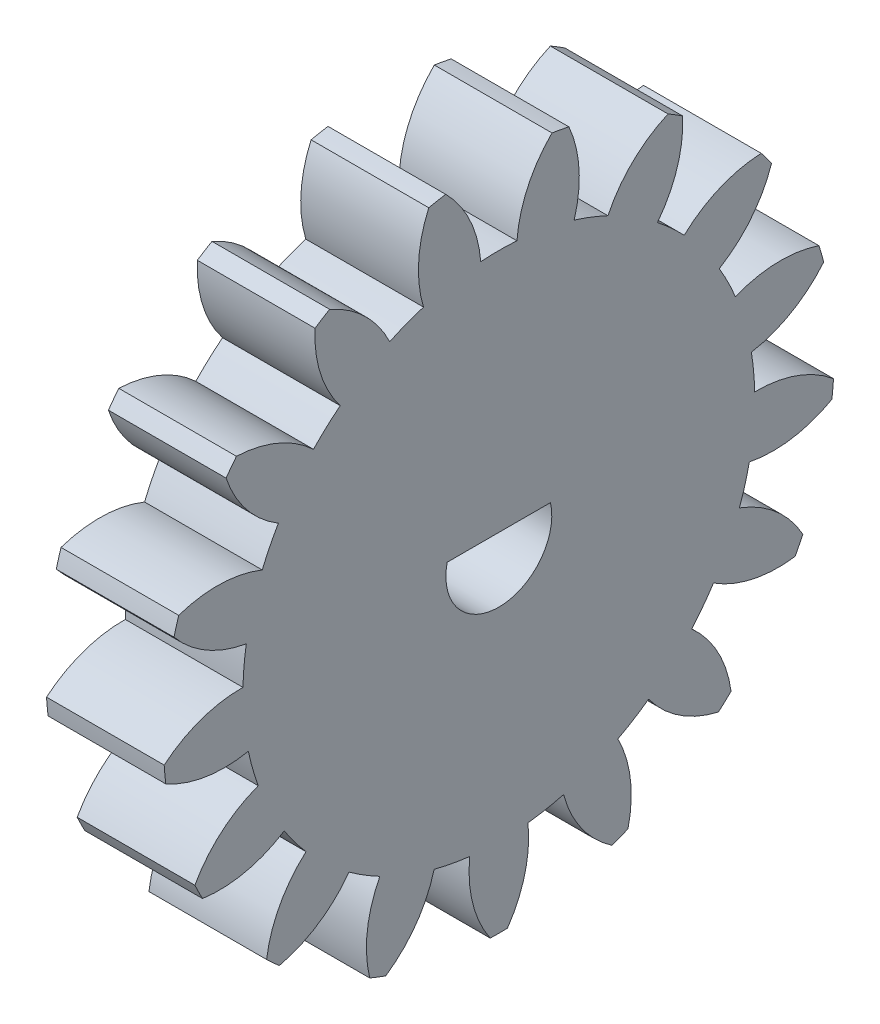
SolidWorks part; units mm, degrees
ref_plane "Plane1" through (0, 0, 0) normal (0, 0, 1) x (1, 0, 0)
ref_plane "Plane2" through (0, 0, 0) normal (0, 1, 0) x (1, 0, 0)
ref_plane "Plane3" through (0, 0, 0) normal (1, 0, 0) x (0, 0, -1)
sketch "HoldingSke" plane through (0, 0, 0) normal (0, 1, 0) x (1, 0, 0)
  line L0 (0, 0) -> (0.6375, -0.1949)
  line L1 (-15, 0) -> (100, 0) construction
  line L2 (0, 0) -> (-2.1039, 2.3779)
  line L3 (0, 0) -> (-11.863, 4.5341)
  line L4 (0, 0) -> (8.2586, 2.5249)
  line L5 (0, 0) -> (-46.8476, -17.4728)
  line L6 (0, 0) -> (-4.1448, -2.7965)
  line L7 (-2.1039, 2.3779) -> (8.6586, 51.2059)
  line L8 (-76.2, 54.61) -> (-76.1, 54.61)
  line L9 (-71.009, 38.7566) -> (-53.1078, 45.2721)
  line L10 (-76.2, 71.12) -> (104.1128, 71.12)
  line L11 (0, 0) -> (-5, 0)
  line L12 (-76.2, 101.6) -> (-76.147, 101.6)
  line L13 (24.9733, 27.94) -> (52.9518, 28.4284)
  line L14 (24.9733, 27.94) -> (24.9743, 27.94)
  line L15 (24.9733, 27.94) -> (100.4006, 29.5858)
  line L16 (-63.627, -1.5) -> (-12.827, -1.5)
  circle A0 centre (0, 0) radius 0.4
  circle A1 centre (0, 0) radius 10.874
  circle A2 centre (0, 0) radius 37.5
  circle A3 centre (0, 0) radius 0.4
  dimension "MHD" = 21.748
  dimension "Hub_dia" = 75
  dimension "Bore" = 0.8
  dimension "MBD" = 0.8
  dimension "Num_teeth" = 17
  dimension "Pitch" = 0.6667
  dimension "Overall_len" = 50
  dimension "Show_teeth" = 17
  dimension "Thickness" = 5
  dimension "OAL" = 50.0001
  dimension "T_dim" = 0.1
  dimension "Ap" = 20
  dimension "H" = 19.05
  dimension "Pitch_radius" = 180.3128
  dimension "Width" = 5
  dimension "Backlash" = 0.053
  dimension "Addendum_fac" = 1
  dimension "Dedendum_fac" = 1.25
  dimension "Clearance_fac" = 0.25
  dimension "Dedendum_add" = 0.001
  dimension "Module" = 1.5
sketch "BasProSke" plane through (0, 0, 0) normal (0, 1, 0) x (1, 0, 0)
  line L0 (-10, 0) -> (60, 0) construction
  line L1 (0, 0) -> (0, 14.25)
  line L2 (0, 0) -> (5, 0)
  line L3 (5, 0) -> (5, 14.25)
  line L4 (5, 14.25) -> (0, 14.25)
  dimension "Thickness" = 5
  dimension "Diameter" = 28.5
revolve "Base-Revolve" add sketch "BasProSke" angle 360 about L0
sketch "TooCutSke" plane through (0, 0, 0) normal (1, 0, 0) x (0, 0, -1)
  line L1 (0, 0) -> (0, 107) construction
  line L2 (0, 0) -> (-1.2691, 12.6867) construction
  line L3 (0, 0) -> (-4.6687, 24.9751) construction
  line L4 (-1.2691, 12.6867) -> (-2.3343, 12.4876) construction
  arc A0 (0.7694, 10.8467) -> (-0.7694, 10.8467) centre (0, 0) ccw
  arc A1 (2.2806, 14.0921) -> (-2.2806, 14.0921) centre (0, 0) ccw
  circle A2 centre (0, 0) radius 12.75 construction
  circle A3 centre (0, 0) radius 11.9811 construction
  arc A4 (-0.7694, 10.8467) -> (-2.2806, 14.0921) centre (-5.8542, 10.4535) ccw
  arc A5 (2.2806, 14.0921) -> (0.7694, 10.8467) centre (5.8542, 10.4535) ccw
  dimension "Root_dia" = 21.748
  dimension "Overcut_dia" = 28.5508
  dimension "Pitch_dia" = 25.5
  dimension "Base_dia" = 23.9622
  dimension "Flank_rad" = 5.1
  dimension "Half_ang" = 10.588
  dimension "Half_CT" = 1.0837
extrude "ToothCut" cut sketch "TooCutSke" along normal through all
fillet "Breaks" [suppressed] radius 0.03
fillet "RootFillets" [suppressed] radius 0.376
pattern_circular "TeethCuts" count 17 every 21.176 about axis through (-10, 0, 0) along (1, 0, 0) of "ToothCut", "RootFillets", "Breaks"
sketch "HubNeaOneSke" plane through (0, 0, 0) normal (-1, 0, 0) x (0, 0, 1)
  circle A0 centre (0, 0) radius 10.874
  dimension "Diameter" = 21.748
extrude "HubNearOne" [suppressed] add sketch "HubNeaOneSke" along normal blind 45.0001
sketch "HubNeaBotSke" plane through (0, 0, 0) normal (-1, 0, 0) x (0, 0, 1)
  circle A0 centre (0, 0) radius 10.874
  dimension "Diameter" = 21.748
extrude "HubNearBoth" [suppressed] add sketch "HubNeaBotSke" along normal blind 22.5
ref_plane "FarPln" through (5, 0, 0) normal (1, 0, 0) x (0, 0, -1)
sketch "HubFarSke" plane through (5, 0, 0) normal (1, 0, 0) x (0, 0, -1)
  circle A0 centre (0, 0) radius 10.874
  dimension "Diameter" = 21.748
extrude "HubFar" [suppressed] add sketch "HubFarSke" along normal blind 22.5
sketch "BorSke" plane through (0, 0, 0) normal (1, 0, 0) x (0, 0, -1)
  circle A0 centre (0, 0) radius 0.4
  dimension "Diameter" = 0.8
extrude "Bore" cut sketch "BorSke" along normal mid plane 100.0001
sketch "KeySke" plane through (0, 0, 0) normal (1, 0, 0) x (0, 0, -1)
  line L0 (-0.05, 0) -> (-0.05, 0.5)
  line L1 (-0.05, 0.5) -> (0.05, 0.5)
  line L2 (0.05, 0.5) -> (0.05, 0)
  line L3 (0, 0) -> (0, 34) construction
  line L4 (-0.05, 0) -> (0.05, 0)
  dimension "Offset" = 0.5
  dimension "Width" = 0.1
extrude "Keyway" [suppressed] cut sketch "KeySke" along normal mid plane 100.0001
pattern_circular "Keyway2" [suppressed] count 2 every 90 about axis through (-10, 0, 0) along (1, 0, 0)
sketch "Sketch1" plane through (5, 0, 0) normal (1, 0, 0) x (0, 0, -1)
  line L0 (-2.1937, 0.5) -> (2.1937, 0.5)
  arc A0 (-2.1937, 0.5) -> (2.1937, 0.5) centre (0, 0) ccw
  point P1 (0, 0)
  dimension "D1" = 4.5
  dimension "D2" = 0.5
extrude "Cut-Extrude1" cut sketch "Sketch1" against normal through all
equation "' \"Module@HoldingSke\" = 6.35"
equation "' \"Num_teeth@HoldingSke\" = 12"
equation "' \"Ap@HoldingSke\" =  20"
equation "' \"Ap@HoldingSke\" = 20"
equation "' \"Width@HoldingSke\" = 0.5 * 25.4"
equation "' \"Hub_dia@HoldingSke\"= 1 * 25.4"
equation "' \"Hub_dia@HoldingSke\" = 1 * 25.4"
equation "' \"Overall_len@HoldingSke\" = 1.0 * 25.4"
equation "' \"Bore@HoldingSke\" = 0.75 * 25.4"
equation "' \"T_dim@HoldingSke\" = 0.1 * 25.4"
equation "' \"Width@KeySke\" = 0.25 * 25.4"
equation "' \"Show_teeth@HoldingSke\" = 13"
equation "' \"Backlash@HoldingSke\" = 0.009 * 25.4"
equation "' \"Addendum_fac@HoldingSke\" = 1.0"
equation "' \"Dedendum_fac@HoldingSke\" = 1.25"
equation "' \"Dedendum_add@HoldingSke\" = 0.00005 * 25.4"
equation "' \"Clearance_fac@HoldingSke\" = 0.25"
equation "\"Pitch@HoldingSke\" = 1 / \"Module@HoldingSke\""
equation "\"Overcut_dia@TooCutSke\" = (\"Num_teeth@HoldingSke\" + 2 * \"Addendum_fac@HoldingSke\") / \"Pitch@HoldingSke\" + 0.002 * 25.4"
equation "\"Pitch_dia@TooCutSke\" = \"Num_teeth@HoldingSke\" / \"Pitch@HoldingSke\""
equation "\"Base_dia@TooCutSke\" = \"Num_teeth@HoldingSke\" / \"Pitch@HoldingSke\" * cos((\"Ap@HoldingSke\"  * 3.14159265 / 180))"
equation "\"Root_dia@TooCutSke\" = (\"Num_teeth@HoldingSke\" + 2) / \"Pitch@HoldingSke\" - 2 * (\"Addendum_fac@HoldingSke\" + \"Dedendum_fac@HoldingSke\") / \"Pitch@HoldingSke\" - \"Dedendum_add@HoldingSke\" * 2"
equation "\"Half_ang@TooCutSke\" = 180 / \"Num_teeth@HoldingSke\""
equation "\"Half_CT@TooCutSke\" = \"Num_teeth@HoldingSke\" / \"Pitch@HoldingSke\" * sin((3.14159265 / 2 / \"Num_teeth@HoldingSke\")) / 2 - 7 * \"Backlash@HoldingSke\" / 4"
equation "\"Flank_rad@TooCutSke\" = \"Num_teeth@HoldingSke\" / \"Pitch@HoldingSke\" / 5"
equation "\"Radius@RootFillets\" = \"Clearance_fac@HoldingSke\" / \"Pitch@HoldingSke\" + \"Dedendum_add@HoldingSke\""
equation "\"Break_rad@Breaks\" = 0.02 / \"Pitch@HoldingSke\""
equation "\"Thickness@HoldingSke\" = \"Width@HoldingSke\""
equation "\"OAL@HoldingSke\" = \"Thickness@HoldingSke\""
equation "\"MHD@HoldingSke\" = (\"Num_teeth@HoldingSke\" + 2) / \"Pitch@HoldingSke\" - 2 * (\"Addendum_fac@HoldingSke\" + \"Dedendum_fac@HoldingSke\")  / \"Pitch@HoldingSke\" - \"Dedendum_add@HoldingSke\" * 2"
equation "\"MBD@HoldingSke\" = (\"Num_teeth@HoldingSke\" + 2) / \"Pitch@HoldingSke\" - 2 * (\"Addendum_fac@HoldingSke\" + \"Dedendum_fac@HoldingSke\")  / \"Pitch@HoldingSke\" - \"Dedendum_add@HoldingSke\" * 2 - 0.002 * 25.4"
equation "\"MHD@HoldingSke\" = ((sgn( \"MHD@HoldingSke\" - \"Hub_dia@HoldingSke\" )-1)*( \"MHD@HoldingSke\" - \"Hub_dia@HoldingSke\" ))/-2+ \"Hub_dia@HoldingSke\""
equation "\"MBD@HoldingSke\" = ((sgn( \"MBD@HoldingSke\" - \"Bore@HoldingSke\" )-1)*( \"MBD@HoldingSke\" - \"Bore@HoldingSke\" ))/-2+ \"Bore@HoldingSke\""
equation "\"OAL@HoldingSke\" = ((sgn( \"OAL@HoldingSke\" - \"Overall_len@HoldingSke\" )+1)*( \"OAL@HoldingSke\" - \"Overall_len@HoldingSke\" ))/2 + \"Overall_len@HoldingSke\" + 0.000002 * 25.4"
equation "\"Num_teeth@TeethCuts\" = int( \"Show_teeth@HoldingSke\" ) + 1"
equation "\"Num_teeth@TeethCuts\" = ((sgn( \"Num_teeth@TeethCuts\" - \"Num_teeth@HoldingSke\" )-1)*( \"Num_teeth@TeethCuts\" - \"Num_teeth@HoldingSke\" ))/-2+ \"Num_teeth@HoldingSke\""
equation "\"Num_teeth@TeethCuts\" = ((sgn( \"Num_teeth@TeethCuts\" - 2.0)+1)*( \"Num_teeth@TeethCuts\" - 2.0))/2 +2.0"
equation "\"Angle@TeethCuts\" = 360.0 / \"Num_teeth@HoldingSke\""
equation "\"Diameter@BasProSke\" = (\"Num_teeth@HoldingSke\" + 2 * \"Addendum_fac@HoldingSke\") / \"Pitch@HoldingSke\""
equation "\"Thickness@BasProSke\"  = \"Thickness@HoldingSke\""
equation "' \"Fillet_rad@BasProSke\" =  \"Thickness@HoldingSke\" * 0.05"
equation "' \"Fillet_rad@BasProSke\" = \"Thickness@HoldingSke\" * 0.05"
equation "\"MHD@HoldingSke\" = ((sgn( \"MHD@HoldingSke\" - \"Root_dia@TooCutSke\" )-1)*( \"MHD@HoldingSke\" - \"Root_dia@TooCutSke\" ))/-2+ \"Root_dia@TooCutSke\""
equation "\"Diameter@HubNeaOneSke\" = \"MHD@HoldingSke\""
equation "\"Length@HubNearOne\" = \"OAL@HoldingSke\" - \"Thickness@BasProSke\""
equation "\"Diameter@HubNeaBotSke\" = \"MHD@HoldingSke\""
equation "\"Length@HubNearBoth\" = ( \"OAL@HoldingSke\" - \"Thickness@BasProSke\" ) / 2.0"
equation "\"Thickness@FarPln\" = \"Thickness@BasProSke\""
equation "\"Diameter@HubFarSke\" = \"MHD@HoldingSke\""
equation "\"Length@HubFar\" = ( \"OAL@HoldingSke\" - \"Thickness@BasProSke\" ) / 2.0"
equation "\"Diameter@BorSke\" = \"MBD@HoldingSke\""
equation "\"D1@Bore\" = \"OAL@HoldingSke\" * 2.0"
equation "\"D1@Keyway\" = \"OAL@HoldingSke\" * 2.0"
equation "\"Offset@KeySke\" = \"T_dim@HoldingSke\" + \"MBD@HoldingSke\" / 2.0"
